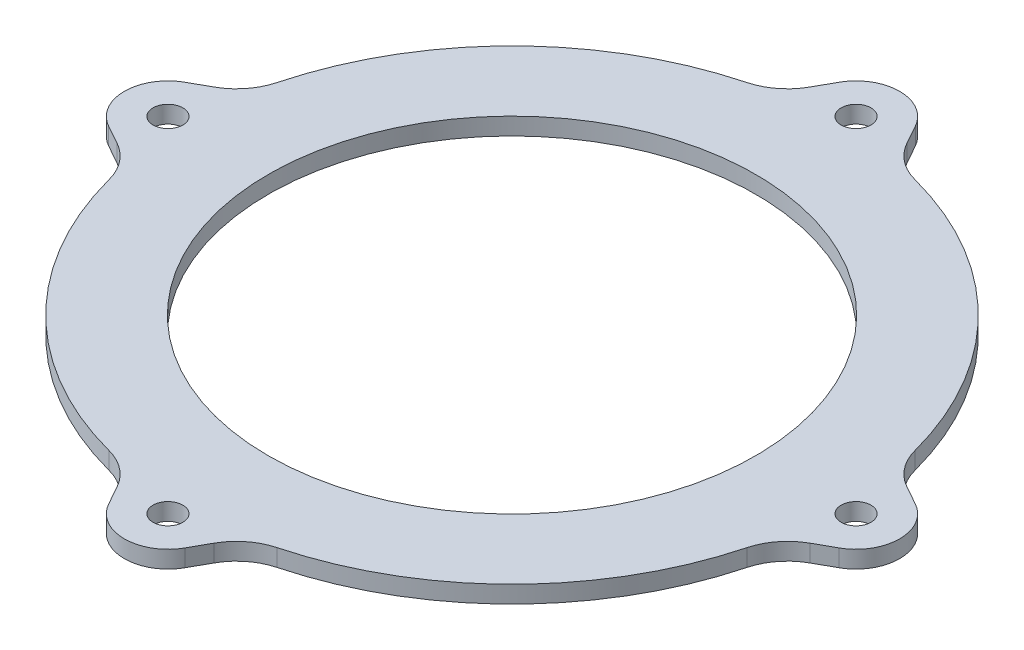
SolidWorks part; units mm, degrees
ref_plane "正面" through (0, 0, 0) normal (0, 0, 1) x (1, 0, 0)
ref_plane "平面" through (0, 0, 0) normal (0, 1, 0) x (1, 0, 0)
ref_plane "右側面" through (0, 0, 0) normal (1, 0, 0) x (0, 0, -1)
sketch "ｽｹｯﾁ1" plane through (0, 0, 0) normal (0, 1, 0) x (1, 0, 0)
  line L0 (0, 0) -> (0, 60) construction
  line L1 (-6.6411, 63.6954) -> (-10.6411, 56.5068)
  line L2 (6.6411, 63.6954) -> (10.6411, 56.5068)
  line L3 (63.6954, 6.6411) -> (56.5068, 10.6411)
  line L4 (63.6954, -6.6411) -> (56.5068, -10.6411)
  line L5 (6.6411, -63.6954) -> (10.6411, -56.5068)
  line L6 (-6.6411, -63.6954) -> (-10.6411, -56.5068)
  line L7 (-63.6954, -6.6411) -> (-56.5068, -10.6411)
  line L8 (-63.6954, 6.6411) -> (-56.5068, 10.6411)
  line L9 (-60, 0) -> (0, 0) construction
  line L10 (0, 0) -> (0, -60) construction
  arc A0 (-10.6411, 56.5068) -> (-56.5068, 10.6411) centre (0, 0) ccw
  circle A1 centre (0, 0) radius 42.5
  circle A2 centre (0, 60) radius 2.6
  arc A3 (6.6411, 63.6954) -> (-6.6411, 63.6954) centre (0, 60) ccw
  circle A4 centre (0, 60) radius 7.6 construction
  circle A5 centre (60, 0) radius 2.6
  arc A6 (63.6954, -6.6411) -> (63.6954, 6.6411) centre (60, 0) ccw
  circle A7 centre (0, -60) radius 2.6
  arc A8 (-6.6411, -63.6954) -> (6.6411, -63.6954) centre (0, -60) ccw
  circle A9 centre (-60, 0) radius 2.6
  arc A10 (-63.6954, 6.6411) -> (-63.6954, -6.6411) centre (-60, 0) ccw
  arc A11 (-56.5068, -10.6411) -> (-10.6411, -56.5068) centre (0, 0) ccw
  arc A12 (10.6411, -56.5068) -> (56.5068, -10.6411) centre (0, 0) ccw
  arc A13 (56.5068, 10.6411) -> (10.6411, 56.5068) centre (0, 0) ccw
  dimension "D1" = 85
  dimension "D2" = 115
  dimension "D3" = 60
  dimension "D4" = 5.2
  dimension "D6" = 4
  dimension "D5" = 5
  dimension "D7" = 4
extrude "ﾎﾞｽ - 押し出し1" add sketch "ｽｹｯﾁ1" along normal blind 3
fillet "ﾌｨﾚｯﾄ1" radius 10 8 edges at (56.5068, 1.5, 10.6411) (56.5068, 1.5, -10.6411) (10.6411, 1.5, -56.5068) (-10.6411, 1.5, -56.5068) (-56.5068, 1.5, -10.6411) (-56.5068, 1.5, 10.6411) (-10.6411, 1.5, 56.5068) (10.6411, 1.5, 56.5068)
